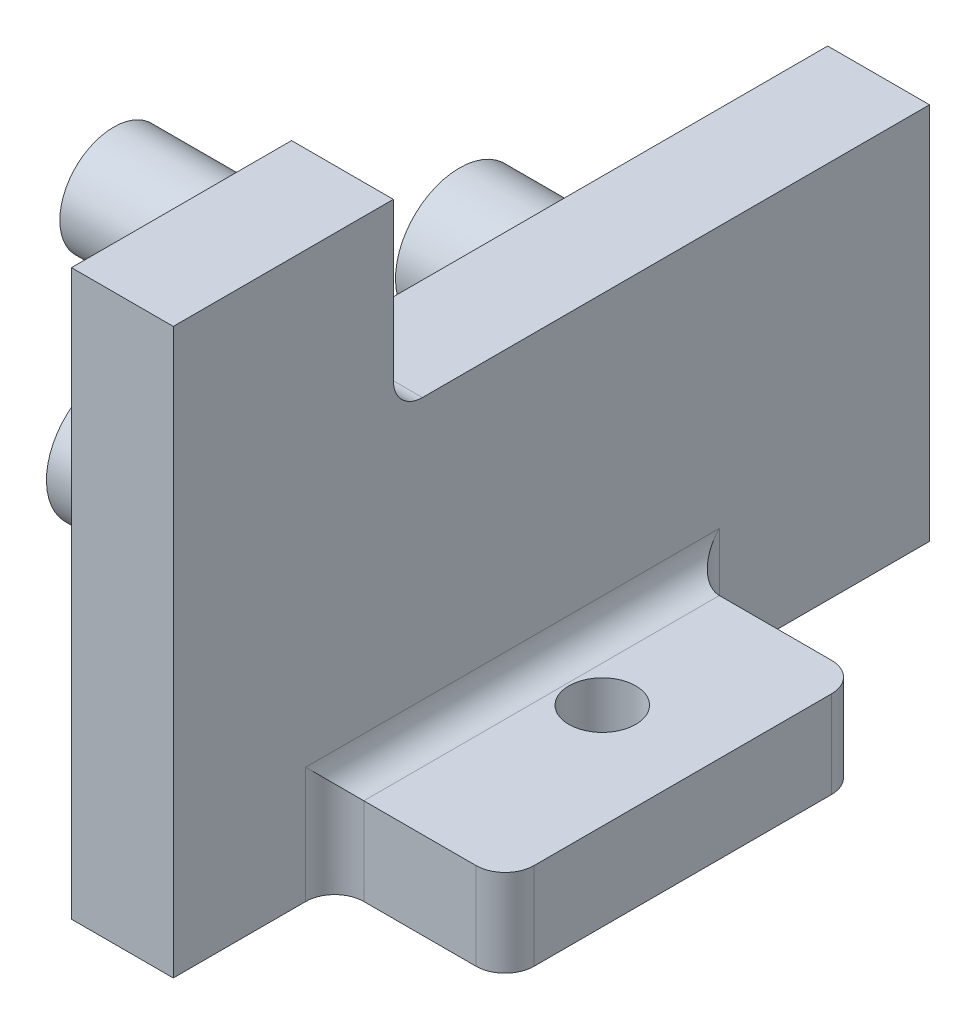
SolidWorks part; units mm, degrees
ref_plane "前视基准面" through (0, 0, 0) normal (0, 0, 1) x (1, 0, 0)
ref_plane "上视基准面" through (0, 0, 0) normal (0, 1, 0) x (1, 0, 0)
ref_plane "右视基准面" through (0, 0, 0) normal (1, 0, 0) x (0, 0, -1)
other "Configuration Table"
sketch "草图1" plane through (0, 0, 0) normal (0, 0, 1) x (1, 0, 0)
  line L1 (-1.1287, 7.4119) -> (2.3713, 7.4119)
  line L2 (-1.1287, 7.4119) -> (-1.1287, -5.5881)
  line L3 (-1.1287, -5.5881) -> (2.3713, -5.5881)
  line L4 (2.3713, 7.4119) -> (2.3713, -5.5881)
  dimension "D1" = 13
  dimension "D2" = 3.5
extrude "凸台-拉伸1" add sketch "草图1" along normal blind 26 contours L2 L3 L4 L1
sketch "草图3" plane through (-1.1287, 0, 0) normal (-1, 0, 0) x (0, 0, 1)
  line L0 (12.16, 10.0619) -> (12.16, -8.8917) construction
  line L1 (26, 7.4119) -> (26, -5.5881) construction
  line L2 (26, -5.5881) -> (0, -5.5881) construction
  circle A0 centre (6.16, 1.4119) radius 2.2
  circle A1 centre (18.16, 1.4119) radius 2.2
  dimension "D1" = 13.84
  dimension "D2" = 7
  dimension "D3" = 12
  dimension "D4" = 12
extrude "凸台-拉伸3" add sketch "草图3" along normal blind 6.5
sketch "草图4" plane through (0, -5.5881, 0) normal (0, -1, 0) x (1, 0, 0)
  line L0 (0.6213, 0) -> (0.6213, 26) construction
  line L1 (-1.1287, 0) -> (2.3713, 0) construction
  line L2 (-1.1287, 26) -> (2.3713, 26) construction
  circle A0 centre (0.6213, 18) radius 0.8
  circle A1 centre (0.6213, 9) radius 0.8
  point P6 (0.6213, 18)
  point P8 (0.6213, 9)
  dimension "D1" = 8
  dimension "D2" = 9
hole_wizard "M2 螺纹孔1" positions "草图4" profile "草图5" tap size "M2" standard "GB"
sketch "草图5" plane through (0.6213, -5.5881, 9) normal (1, 0, 0) x (0, 0, -1)
  line L0 (0, 0) -> (0, 6.4807)
  line L1 (0, 6.4807) -> (0.8, 6)
  line L2 (0.8, 6) -> (0.8, 0)
  line L5 (0.8, 0) -> (0, 0)
  line L10 (0, 6.4807) -> (-0.8, 6) construction
  line L11 (0, -6.35) -> (0, 107.95) construction
  dimension "螺纹孔钻头直径" = 1.6
  dimension "螺纹孔钻头深度" = 6
  dimension "导头角度" = 118
cosmetic thread "孔螺蚊线1" parameters "D1"=4, "D2"=2
cosmetic thread "孔螺蚊线2" parameters "D1"=4, "D2"=2
sketch "草图6" plane through (0, -5.5881, 0) normal (0, -1, 0) x (1, 0, 0)
  line L0 (2.3713, 26) -> (2.3713, 0) construction
  line L1 (2.3713, 20.4475) -> (8.2258, 20.4475)
  line L2 (2.3713, 20.4475) -> (2.3713, 8.2247)
  line L3 (2.3713, 8.2247) -> (8.2258, 8.2247)
  line L4 (8.2258, 20.4475) -> (8.2258, 8.2247)
extrude "凸台-拉伸4" add sketch "草图6" against normal blind 3
sketch "草图7" plane through (0, -5.5881, 0) normal (0, -1, 0) x (1, 0, 0)
  line L0 (0.6213, 18) -> (0.6213, 9) construction
  line L1 (0.6213, 13.5) -> (10.4206, 13.5) construction
  circle A0 centre (4.6213, 13.5) radius 1.05
  point P6 (4.6213, 13.5)
  dimension "D1" = 4
hole_wizard "Ø2.0mm 暗销孔1" positions "草图7" profile "草图8" hole size "Ø2.0" standard "GB"
sketch "草图8" plane through (4.6213, -5.5881, 13.5) normal (1, 0, 0) x (0, 0, -1)
  line L0 (0, 0) -> (0, 4.841)
  line L1 (0, 4.841) -> (1.15, 4.15)
  line L2 (1.15, 4.15) -> (1.15, 0)
  line L5 (1.15, 0) -> (0, 0)
  line L10 (0, 4.841) -> (-1.15, 4.15) construction
  line L11 (0, -6.35) -> (0, 107.95) construction
  dimension "孔直径" = 2.3
  dimension "孔深度" = 4.15
  dimension "导头角度" = 118
fillet "圆角2" radius 1 1 edges at (2.3713, -2.5881, 14.3361)
fillet "圆角3" radius 1 2 edges at (2.3713, -3.5881, 20.4475) (2.6642, -2.2952, 20.4475)
fillet "圆角4" radius 1 2 edges at (2.3713, -3.5881, 8.2247) (2.6642, -2.2952, 8.2247)
fillet "圆角5" radius 1 1 edges at (8.2258, -4.0881, 8.2247)
fillet "圆角6" radius 1 1 edges at (8.2258, -4.0881, 20.4475)
ref_plane "基准面1" through (0, 0, 12.5) normal (0, 0, 1) x (1, 0, 0)
sketch "草图9" plane through (-1.1287, 0, 0) normal (-1, 0, 0) x (0, 0, 1)
  line L1 (26, 7.4119) -> (18.4337, 7.4119)
  line L2 (26, 7.4119) -> (26, 13.8129)
  line L3 (26, 13.8129) -> (18.4337, 13.8129)
  line L4 (18.4337, 7.4119) -> (18.4337, 13.8129)
extrude "凸台-拉伸5" add sketch "草图9" against normal up to surface (3.5 mm away) up to face at (2.3713, -1.3381, 13.668)
sketch "草图10" plane through (-1.1287, 0, 0) normal (-1, 0, 0) x (0, 0, 1)
  line L0 (26, 13.8129) -> (26, -5.5881) construction
  line L1 (26, 13.8129) -> (18.4337, 13.8129) construction
  circle A0 centre (20.85, 11.7229) radius 1.85
  dimension "D1" = 5.15
  dimension "D2" = 2.09
extrude "凸台-拉伸6" add sketch "草图10" along normal blind 3.7 contours A0
fillet "圆角7" radius 1 1 edges at (0.6213, 7.4119, 18.4337)
